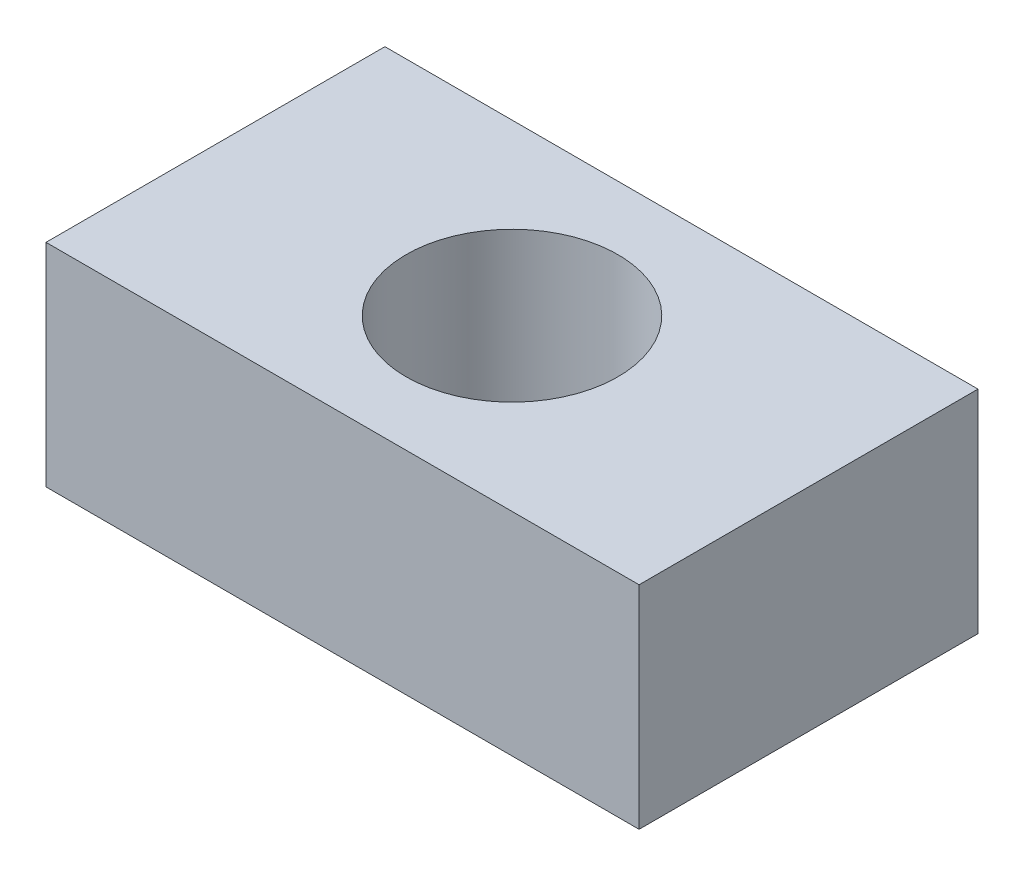
SolidWorks part; units mm, degrees
ref_plane "Front Plane" through (0, 0, 0) normal (0, 0, 1) x (1, 0, 0)
ref_plane "Top Plane" through (0, 0, 0) normal (0, 1, 0) x (1, 0, 0)
ref_plane "Right Plane" through (0, 0, 0) normal (1, 0, 0) x (0, 0, -1)
sketch "Sketch1" plane through (0, 0, 0) normal (0, 1, 0) x (1, 0, 0)
  line L1 (-7, -4) -> (7, -4)
  line L2 (-7, -4) -> (-7, 4)
  line L3 (-7, 4) -> (7, 4)
  line L4 (7, -4) -> (7, 4)
  line L5 (-7, -4) -> (7, 4) construction
  line L6 (-7, 4) -> (7, -4) construction
  circle A0 centre (0, 0) radius 2.5
  point P0 (0, 0)
  dimension "D1" = 5
  dimension "D2" = 8
  dimension "D3" = 14
extrude "Boss-Extrude1" add sketch "Sketch1" along normal mid plane 5
